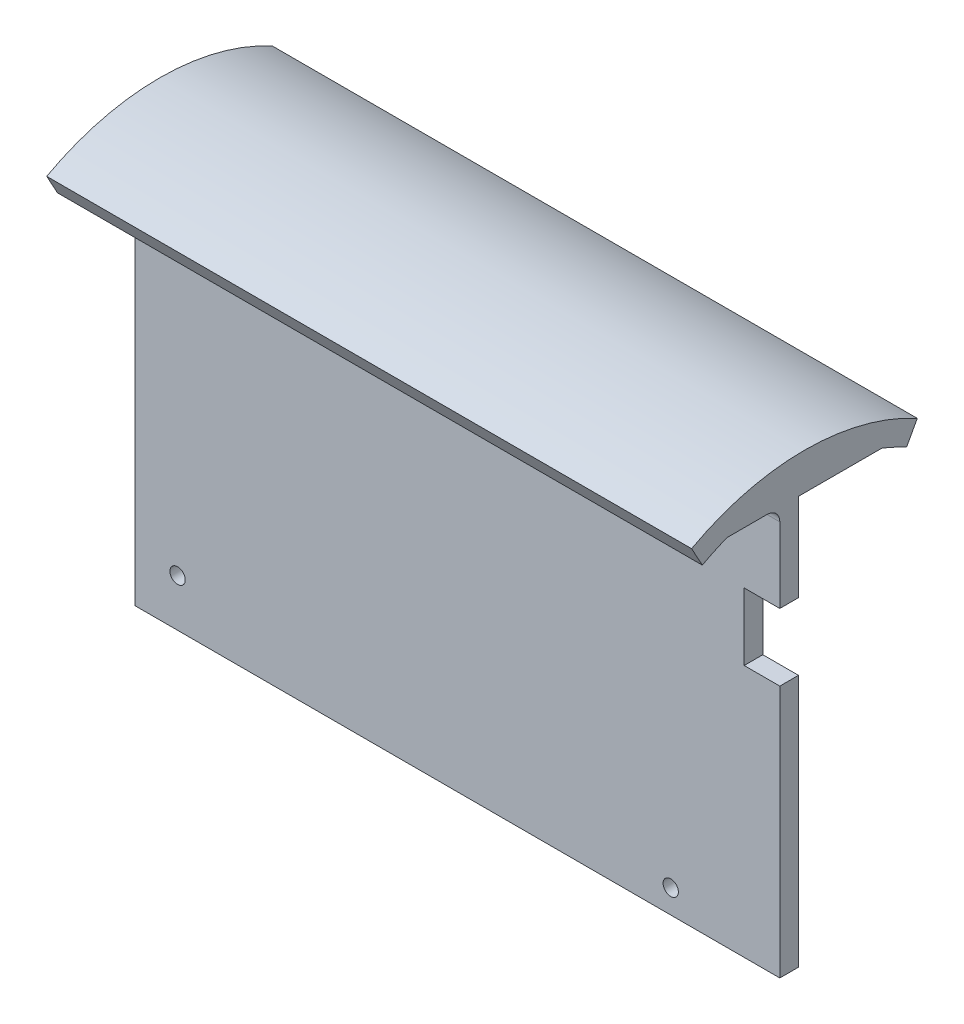
SolidWorks part; units mm, degrees
ref_plane "Plano frontal" through (0, 0, 0) normal (0, 0, 1) x (1, 0, 0)
ref_plane "Plano superior" through (0, 0, 0) normal (0, 1, 0) x (1, 0, 0)
ref_plane "Plano direito" through (0, 0, 0) normal (1, 0, 0) x (0, 0, -1)
sketch "Esboço1" plane through (0, 0, 0) normal (0, 0, 1) x (1, 0, 0)
  line L4 (-18.3229, 24.2872) -> (-18.3229, 16.6872) construction
  line L5 (-4.2276, 24.2561) -> (-4.2276, 18.5561) construction
  line L6 (36.83, 26.5501) -> (-30.48, 26.5501)
  line L7 (-43.18, 13.8501) -> (-43.18, -15.3599)
  line L8 (-30.48, -28.0599) -> (36.83, -28.0599)
  line L9 (43.18, -21.7099) -> (43.18, 5.7941)
  line L10 (20.8444, 21.7291) -> (20.8444, 16.0291) construction
  line L11 (38.9427, 9.0841) -> (38.9427, 11.5041)
  line L12 (38.9427, 10.2941) -> (44.3727, 10.2941) construction
  line L13 (43.18, 14.7941) -> (43.18, 20.2001)
  line L14 (43.18, 14.7941) -> (38.4077, 14.7941)
  line L15 (38.4077, 14.7941) -> (44.9077, 14.7941) construction
  line L16 (38.4077, 14.7941) -> (38.4077, 5.7941) construction
  line L17 (38.4077, 5.7941) -> (44.9077, 5.7941) construction
  line L18 (44.9077, 14.7941) -> (44.9077, 5.7941) construction
  line L19 (38.4077, 14.7941) -> (44.9077, 5.7941) construction
  line L20 (38.4077, 5.7941) -> (44.9077, 14.7941) construction
  line L21 (38.4077, 14.7941) -> (38.4077, 5.7941)
  line L22 (38.4077, 5.7941) -> (43.18, 5.7941)
  line L23 (-43.18, 0) -> (43.18, 0) construction
  line L24 (-43.18, 13.8501) -> (-43.18, 26.5501)
  line L25 (-43.18, 26.5501) -> (-30.48, 26.5501)
  line L26 (43.18, 20.2001) -> (43.18, 26.5501)
  line L27 (43.18, 26.5501) -> (36.83, 26.5501)
  line L28 (-43.18, -15.3599) -> (-43.18, -28.0599)
  line L29 (-43.18, -28.0599) -> (-30.48, -28.0599)
  line L30 (43.18, -21.7099) -> (43.18, -28.0599)
  line L31 (43.18, -28.0599) -> (36.83, -28.0599)
  arc A0 (43.18, 20.2001) -> (36.83, 26.5501) centre (36.83, 20.2001) ccw construction
  arc A1 (-30.48, 26.5501) -> (-43.18, 13.8501) centre (-30.48, 13.8501) ccw construction
  arc A2 (-43.18, -15.3599) -> (-30.48, -28.0599) centre (-30.48, -15.3599) ccw construction
  arc A3 (36.83, -28.0599) -> (43.18, -21.7099) centre (36.83, -21.7099) ccw construction
  circle A4 centre (-37.465, -21.7099) radius 1.5875 construction
  circle A5 centre (28.575, -24.8849) radius 1.5875 construction
  circle A6 centre (28.575, 23.3751) radius 1.5875 construction
  circle A7 centre (-37.465, 20.2001) radius 1.5875 construction
  circle A8 centre (-18.3229, 20.4872) radius 5
  circle A9 centre (-4.2276, 21.4061) radius 4
  circle A10 centre (20.8444, 18.8791) radius 4
  point P37 (41.6577, 10.2941)
  point P46 (0, 0)
  dimension "D5" = 8
  dimension "D3" = 10
  dimension "D4" = 8
  dimension "D1" = 9
  dimension "D2" = 6.5
extrude "Ressalto-extrusão4" add sketch "Esboço1" along normal blind 2.5 contours L8 A3 L9 L22 L21 L14 L13 A0 L6 A1 L7 A2 A10 A9 A8 A7 A6 A5 A4
sketch "Esboço7" plane through (0, 0, 0) normal (0, 0, -1) x (-1, 0, 0)
  circle A3 centre (37.465, -21.7099) radius 1.5875 construction
  circle A4 centre (37.465, 20.2001) radius 1.5875 construction
  circle A5 centre (-28.575, 23.3751) radius 1.5875 construction
  circle A7 centre (-28.575, -24.8849) radius 1.5875 construction
  circle A8 centre (37.465, -21.7099) radius 3.0875
  circle A9 centre (37.465, 20.2001) radius 3.0875
  circle A10 centre (-28.575, 23.3751) radius 3.0875
  circle A11 centre (-28.575, -24.8849) radius 3.0875
  dimension "D1" = 1.5
extrude "Ressalto-extrusão5" add sketch "Esboço7" along normal blind 2.5
hole_wizard "Broca de rosquear para tarraxa de M2.51" positions "3DSketch1" profile "Esboço8" hole size "M2.5" standard "DIN" end condition through all
sketch3d "3DSketch1"
  line L0 (28.575, 23.3751, -2.5) -> (28.575, 23.3751, 0) construction
  line L1 (-37.465, 20.2001, -2.5) -> (-37.465, 20.2001, 0) construction
  line L2 (28.575, -24.8849, -2.5) -> (28.575, -24.8849, 0) construction
  line L3 (-37.465, -21.7099, -2.5) -> (-37.465, -21.7099, 0) construction
  point P0 (28.575, 23.3751, -2.5)
  point P4 (-37.465, 20.2001, -2.5)
  point P8 (28.575, -24.8849, -2.5)
  point P12 (-37.465, -21.7099, -2.5)
sketch "Esboço8" plane through (28.575, 23.3751, -2.5) normal (1, 0, 0) x (0, 1, 0)
  line L0 (0, 0) -> (0, 5)
  line L1 (0, 5) -> (1.025, 5)
  line L2 (1.025, 5) -> (1.025, 0)
  line L5 (1.025, 0) -> (0, 0)
  line L11 (0, -6.35) -> (0, 107.95) construction
  dimension "Thru Hole Dia." = 2.05
  dimension "Thru Hole Depth" = 5
sketch "Esboço9" plane through (-43.18, 0, 0) normal (-1, 0, 0) x (0, 0, 1)
  line L0 (-2.5, 17.1126) -> (-2.5, -18.6224) construction
  line L1 (-4.1, 17.1126) -> (-4.1, -18.6224) construction
  line L2 (2.5, 0) -> (-4.1, 0) construction
  line L3 (2.5, -28.0599) -> (2.5, 26.5501) construction
  line L4 (-15.9127, 27.6379) -> (14.3127, 27.6379) construction
  line L5 (-0.8, 0) -> (14.3127, 27.6379) construction
  line L6 (-0.8, 0) -> (-15.9127, 27.6379) construction
  line L7 (2.5, 24.8366) -> (2.5, 26.5501)
  line L8 (0, 26.5501) -> (2.5, 26.5501)
  line L9 (-14.4734, 25.0057) -> (-15.9127, 27.6379)
  line L10 (12.8734, 25.0057) -> (14.3127, 27.6379)
  line L11 (4.2134, 26.5501) -> (9.5607, 26.5501)
  line L12 (0, 26.5501) -> (-11.1607, 26.5501)
  arc A0 (-15.9127, 27.6379) -> (14.3127, 27.6379) centre (-0.8, 0) cw
  arc A1 (-14.4734, 25.0057) -> (-11.1607, 26.5501) centre (-0.8, 0) cw
  arc A4 (9.5607, 26.5501) -> (12.8734, 25.0057) centre (-0.8, 0) cw
  arc A5 (2.5, 24.8366) -> (4.2134, 26.5501) centre (4.2134, 24.8366) cw
  arc A6 (-14.4734, 25.0057) -> (12.8734, 25.0057) centre (-0.8, 0) cw construction
  point P13 (-0.8, 0)
  dimension "D2" = 31.5
  dimension "D3" = 3
  dimension "D1" = 1.6
extrude "Ressalto-extrusão6" add sketch "Esboço9" against normal up to surface (86.36 mm away) contours L7 L8 L12 A1 L9 A0 L10 A4 L11 A5 up to face at (43.18, 20.6721, 1.25)
